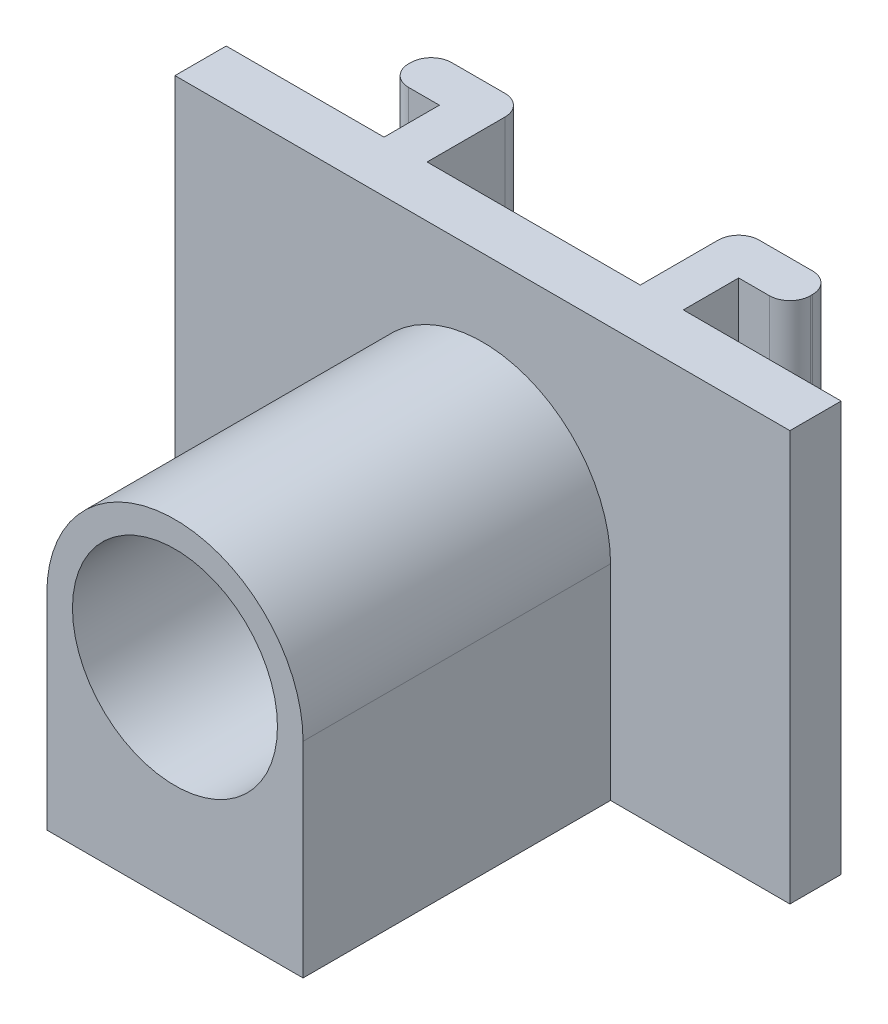
SolidWorks part; units mm, degrees
ref_plane "Front Plane" through (0, 0, 0) normal (0, 0, 1) x (1, 0, 0)
ref_plane "Top Plane" through (0, 0, 0) normal (0, 1, 0) x (1, 0, 0)
ref_plane "Right Plane" through (0, 0, 0) normal (1, 0, 0) x (0, 0, -1)
sketch "Sketch1" plane through (0, 0, 0) normal (0, 0, 1) x (1, 0, 0)
  line L1 (-19.05, -12.7) -> (19.05, -12.7)
  line L2 (-19.05, -12.7) -> (-19.05, 12.7)
  line L3 (-19.05, 12.7) -> (19.05, 12.7)
  line L4 (19.05, -12.7) -> (19.05, 12.7)
  line L5 (-19.05, -12.7) -> (19.05, 12.7) construction
  line L6 (-19.05, 12.7) -> (19.05, -12.7) construction
  point P0 (0, 0)
  dimension "D1" = 25.4
  dimension "D2" = 38.1
extrude "Boss-Extrude1" add sketch "Sketch1" along normal blind 3.175
sketch "Sketch2" plane through (0, 0, 0) normal (0, 0, -1) x (-1, 0, 0)
  line L0 (0, -12.7) -> (0, 12.7) construction
  line L1 (19.05, -12.7) -> (-19.05, -12.7) construction
  line L2 (-19.05, 12.7) -> (19.05, 12.7) construction
  line L3 (-19.05, -12.7) -> (-19.05, 12.7) construction
  line L4 (-12.7, 12.7) -> (12.7, 12.7)
  line L5 (-12.7, 12.7) -> (-12.7, -12.7)
  line L6 (-12.7, -12.7) -> (12.7, -12.7)
  line L7 (12.7, 12.7) -> (12.7, -12.7)
  dimension "D1" = 6.35
extrude "Boss-Extrude2" add sketch "Sketch2" along normal blind 6.35
ref_plane "Plane1" through (0, 0, 0) normal (-1, 0, 0) x (0, 0, 1)
sketch "Sketch3" plane through (0, 12.7, 0) normal (0, 1, 0) x (1, 0, 0)
  line L0 (-12.7, 6.35) -> (12.7, 6.35) construction
  line L1 (12.7, 0) -> (9.525, 0)
  line L2 (12.7, 0) -> (12.7, 3.175)
  line L3 (12.7, 3.175) -> (9.525, 3.175)
  line L4 (9.525, 0) -> (9.525, 3.175)
  line L5 (6.35, 6.35) -> (0, 6.35)
  line L6 (6.35, 6.35) -> (6.35, 0)
  line L7 (6.35, 0) -> (0, 0)
  line L8 (0, 6.35) -> (0, 0)
  dimension "D1" = 3.175
  dimension "D2" = 3.175
  dimension "D3" = 3.175
  dimension "D4" = 6.35
extrude "Cut-Extrude1" cut sketch "Sketch3" against normal up to next
sketch "Sketch4" plane through (0, 12.7, 0) normal (0, 1, 0) x (1, 0, 0)
  line L15 (6.604, 0) -> (6.35, 0)
  line L16 (6.35, 0) -> (6.35, 6.35)
  line L17 (6.35, 6.35) -> (12.7, 6.35)
  line L18 (12.7, 6.35) -> (12.7, 3.175)
  line L19 (12.7, 3.175) -> (9.525, 3.175)
  line L20 (6.604, 0) -> (6.604, 6.096)
  line L21 (6.604, 6.096) -> (12.446, 6.096)
  line L22 (12.446, 6.096) -> (12.446, 3.429)
  line L23 (12.446, 3.429) -> (9.271, 3.429)
  line L24 (9.271, 3.429) -> (9.271, 0)
  line L25 (6.604, 0) -> (6.604, 6.096)
  line L26 (6.604, 6.096) -> (12.446, 6.096)
  line L27 (12.446, 6.096) -> (12.446, 3.429)
  line L28 (12.446, 3.429) -> (9.271, 3.429)
  line L29 (9.271, 3.429) -> (9.271, 0)
  line L30 (9.525, 3.175) -> (9.525, 0)
  line L31 (9.525, 0) -> (9.271, 0)
  dimension "D1" = 0.254
extrude "Cut-Extrude2" cut sketch "Sketch4" against normal up to next
mirror "Mirror1" about plane through (0, 0, 0) normal (-1, 0, 0) of "Cut-Extrude2", "Cut-Extrude1"
fillet "Fillet1" radius 1.27 6 edges at (-6.604, 0, -6.096) (-12.446, 0, -3.429) (-12.446, 0, -6.096) (12.446, 0, -3.429) (12.446, 0, -6.096) (6.604, 0, -6.096)
sketch "Sketch5" plane through (0, 0, 3.175) normal (0, 0, 1) x (1, 0, 0)
  line L1 (7.9375, 0) -> (7.9375, -12.7)
  line L2 (-19.05, -12.7) -> (19.05, -12.7) construction
  line L3 (7.9375, -12.7) -> (-7.9375, -12.7)
  line L4 (-7.9375, -12.7) -> (-7.9375, 0)
  arc A0 (-7.9375, 0) -> (7.9375, 0) centre (0, 0) cw
  dimension "D1" = 15.875
extrude "Boss-Extrude3" add sketch "Sketch5" along normal blind 19.05
sketch "Sketch6" plane through (0, 0, 22.225) normal (0, 0, 1) x (1, 0, 0)
  circle A0 centre (0, 0) radius 6.35
  dimension "D1" = 12.7
extrude "Cut-Extrude3" cut sketch "Sketch6" against normal up to next
